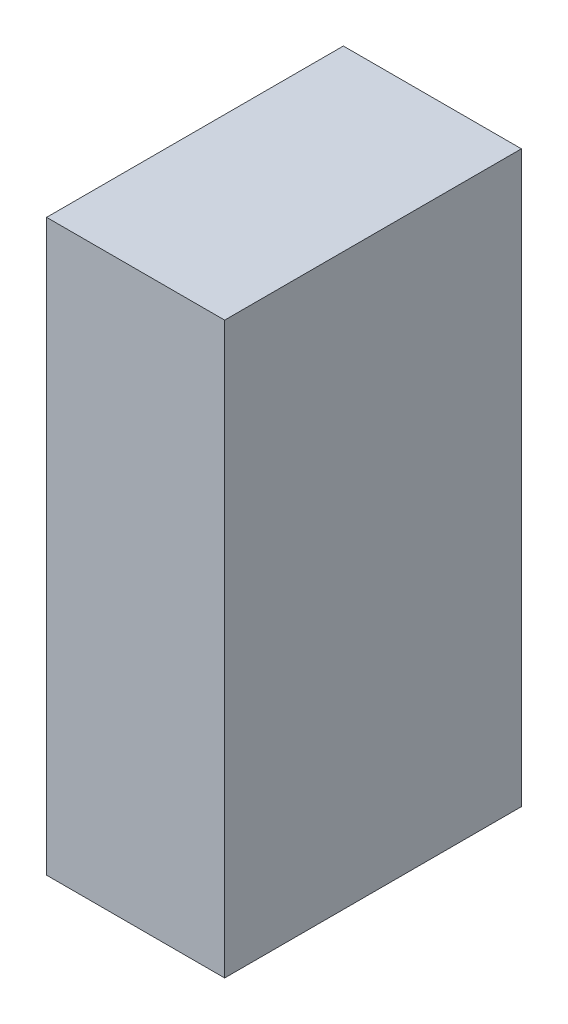
SolidWorks part; units mm, degrees
ref_plane "Front Plane" through (0, 0, 0) normal (0, 0, 1) x (1, 0, 0)
ref_plane "Top Plane" through (0, 0, 0) normal (0, 1, 0) x (1, 0, 0)
ref_plane "Right Plane" through (0, 0, 0) normal (1, 0, 0) x (0, 0, -1)
sketch "Sketch1" plane through (0, 0, 0) normal (0, 1, 0) x (1, 0, 0)
  line L1 (0, 0) -> (15, 0)
  line L2 (0, 0) -> (0, 25)
  line L3 (0, 25) -> (15, 25)
  line L4 (15, 0) -> (15, 25)
  dimension "D1" = 25
  dimension "D2" = 15
extrude "Boss-Extrude1" add sketch "Sketch1" along normal blind 48
